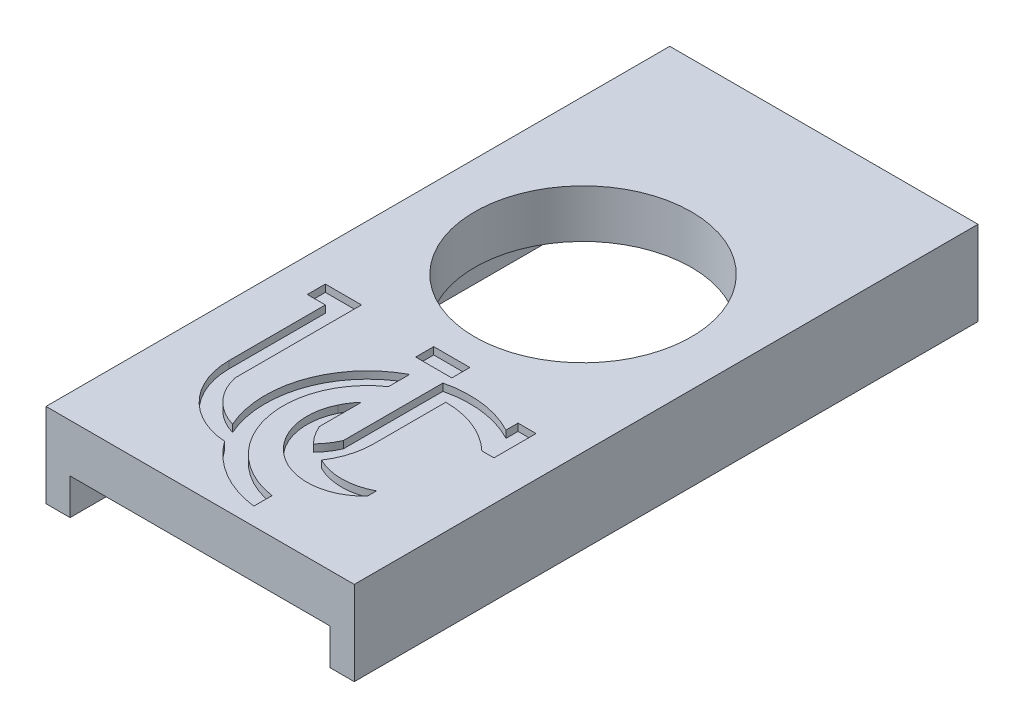
SolidWorks part; units mm, degrees
ref_plane "Front Plane" through (0, 0, 0) normal (0, 0, 1) x (1, 0, 0)
ref_plane "Top Plane" through (0, 0, 0) normal (0, 1, 0) x (1, 0, 0)
ref_plane "Right Plane" through (0, 0, 0) normal (1, 0, 0) x (0, 0, -1)
sketch "Sketch1" plane through (0, 0, 0) normal (0, 1, 0) x (1, 0, 0)
  line L1 (-6.4, 12.95) -> (6.4, 12.95)
  line L2 (-6.4, 12.95) -> (-6.4, -12.95)
  line L3 (-6.4, -12.95) -> (6.4, -12.95)
  line L4 (6.4, 12.95) -> (6.4, -12.95)
  line L5 (-5.4, 10.95) -> (5.4, 10.95)
  line L6 (-5.4, 10.95) -> (-5.4, -10.95)
  line L7 (-5.4, -10.95) -> (5.4, -10.95)
  line L8 (5.4, 10.95) -> (5.4, -10.95)
  point P8 (-5.4, 0)
  point P9 (0, 10.95)
  dimension "D1" = 1
  dimension "D2" = 2
  dimension "D3" = 1
  dimension "D4" = 2
  dimension "D5" = 12.8
  dimension "D6" = 25.9
extrude "Boss-Extrude1" add sketch "Sketch1" along normal blind 3.5
sketch "Sketch3" plane through (0, 0, 0) normal (0, 0, 1) x (1, 0, 0)
  line L1 (-5.4, 1.5) -> (5.4, 1.5)
  line L2 (-5.4, 1.5) -> (-5.4, 0)
  line L3 (-5.4, 0) -> (5.4, 0)
  line L4 (5.4, 1.5) -> (5.4, 0)
  point P4 (0, 0)
  dimension "D1" = 10.8
  dimension "D2" = 1.5
extrude "Cut-Extrude1" cut sketch "Sketch3" along normal through all
ref_plane "Plane1" through (0, 3.5, 0) normal (0, 1, 0) x (1, 0, 0)
sketch "Sketch4" plane through (0, 3.5, 0) normal (0, 1, 0) x (1, 0, 0)
  line L0 (6.4, 12.95) -> (-6.4, 12.95) construction
  line L1 (-5.4, 10.95) -> (5.4, 10.95)
  line L2 (-5.4, 10.95) -> (-5.4, -10.95)
  line L3 (-5.4, -10.95) -> (5.4, -10.95)
  line L4 (5.4, 10.95) -> (5.4, -10.95)
  circle A0 centre (0, 2.95) radius 4.5
  dimension "D1" = 9
  dimension "D2" = 10
extrude "Boss-Extrude2" add sketch "Sketch4" against normal blind 2
sketch "Sketch5" plane through (0, 3.5, 0) normal (0, 1, 0) x (1, 0, 0)
  line L0 (0, -3.1776) -> (0, -10.8637) construction
  line L1 (-5.4351, -7) -> (4.3244, -7) construction
  line L2 (0, -6.25) -> (0, -8)
  line L3 (1, -8) -> (1, -3.8693)
  line L4 (1.75, -4.5) -> (1.75, -7.5)
  line L5 (4, -4.25) -> (4, -3.75)
  line L6 (4, -3.75) -> (4.75, -3.75)
  line L7 (4.75, -3.75) -> (4.75, -5.5)
  line L8 (4.75, -5.5) -> (4.25, -5.5)
  line L9 (-4.25, -3.5) -> (-4.25, -7.5)
  line L10 (1, -2.75) -> (-0.5, -2.75)
  line L11 (1, -2.75) -> (1, -3.5)
  line L12 (1, -3.5) -> (-0.5, -3.5)
  line L13 (-0.5, -2.75) -> (-0.5, -3.5)
  line L14 (-4.25, -3.5) -> (-5, -3.5)
  line L15 (-5, -3.5) -> (-5, -2.75)
  line L16 (-5, -2.75) -> (-3.5, -2.75)
  line L17 (-3.5, -2.75) -> (-3.5, -8)
  line L18 (0, -4.25) -> (0, -5.1277)
  line L19 (3.5, -9.5) -> (3.5, -9.1247)
  line L20 (1.5, -12.2205) -> (1.5, -11.4641)
  arc A0 (4, -4.25) -> (1, -3.8693) centre (2, -8) ccw
  arc A1 (1.75, -4.5) -> (4.25, -5.5) centre (1.75, -8.125) cw
  arc A2 (-1.4414, -10.4939) -> (1.5, -12.2205) centre (2, -8) ccw
  arc A3 (0, -4.25) -> (-1.8888, -9.7146) centre (2, -8) ccw
  arc A4 (0, -5.1277) -> (1.5, -11.4641) centre (2, -8) ccw
  arc A5 (-3.5, -8) -> (-1.8888, -9.7146) centre (-1.25, -7.5) ccw
  arc A6 (-4.25, -7.5) -> (-1.4414, -10.4939) centre (-1.25, -7.5) ccw
  arc A7 (0, -6.25) -> (-0.3919, -6.8418) centre (2, -8) ccw
  arc A8 (3.5, -9.5) -> (-0.3919, -6.8418) centre (1.7526, -7.8802) cw
  arc A9 (1.75, -7.5) -> (1.25, -9.1583) centre (-1.25, -7.5) cw
  arc A10 (1.25, -9.1583) -> (3.5, -9.1247) centre (2.3427, -6.9799) ccw
  arc A11 (0, -8) -> (0.5, -8.75) centre (2.3427, -6.9799) ccw
  arc A12 (1, -8) -> (0.5, -8.75) centre (-1.3427, -6.9799) cw
  point P7 (0.5, -8.75)
  point P27 (3.5, -9.5)
  point P38 (2, -4)
  point P39 (2, -10.25)
  dimension "D11" = 4
  dimension "D24" = 4.25
  dimension "D8" = 4.25
  dimension "D31" = 4.25
  dimension "D32" = 3.5
  dimension "D33" = 3
  dimension "D34" = 2.5
  dimension "D35" = 3.5
  dimension "D40" = 1.25
  dimension "D1" = 7
  dimension "D2" = 1
  dimension "D3" = 0.75
  dimension "D4" = 0.5
  dimension "D5" = 1.75
  dimension "D6" = 1
  dimension "D7" = 1
  dimension "D9" = 2
  dimension "D10" = 1
  dimension "D12" = 0.75
  dimension "D13" = 2.5
  dimension "D14" = 0.5
  dimension "D15" = 0.75
  dimension "D16" = 1.75
  dimension "D17" = 0.5
  dimension "D18" = 1
  dimension "D19" = 1.5
  dimension "D20" = 0.75
  dimension "D21" = 3.5
  dimension "D22" = 0.5
  dimension "D23" = 1.25
  dimension "D25" = 4.25
  dimension "D26" = 0.75
  dimension "D27" = 1.5
  dimension "D28" = 3.5
  dimension "D29" = 3.5
  dimension "D30" = 1
  dimension "D36" = 3.25
  dimension "D37" = 2
  dimension "D38" = 1.5
  dimension "D39" = 0.3753
extrude "Cut-Extrude2" cut sketch "Sketch5" against normal blind 0.3
